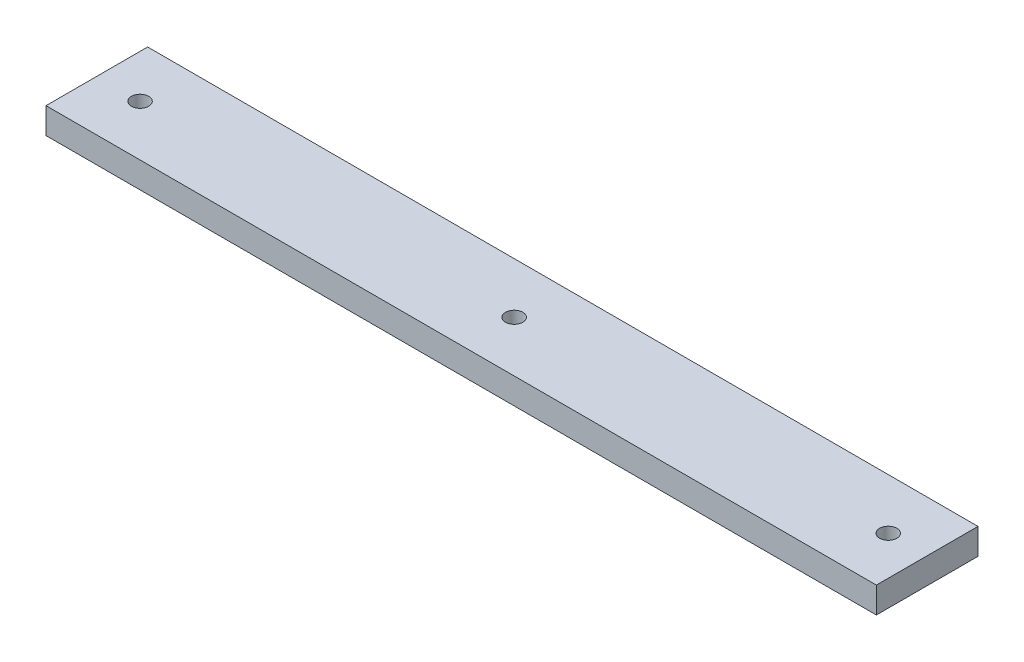
SolidWorks part; units mm, degrees
ref_plane "Front Plane" through (0, 0, 0) normal (0, 0, 1) x (1, 0, 0)
ref_plane "Top Plane" through (0, 0, 0) normal (0, 1, 0) x (1, 0, 0)
ref_plane "Right Plane" through (0, 0, 0) normal (1, 0, 0) x (0, 0, -1)
sketch "Sketch1" plane through (0, 0, 0) normal (0, 1, 0) x (1, 0, 0)
  line L1 (304.8, -37.3062) -> (-304.8, -37.3063)
  line L2 (304.8, -37.3062) -> (304.8, 37.3063)
  line L3 (304.8, 37.3063) -> (-304.8, 37.3062)
  line L4 (-304.8, -37.3063) -> (-304.8, 37.3062)
  line L5 (304.8, -37.3062) -> (-304.8, 37.3062) construction
  line L6 (304.8, 37.3063) -> (-304.8, -37.3063) construction
  point P0 (0, 0)
  dimension "D1" = 609.6
  dimension "D2" = 74.6125
extrude "Boss-Extrude1" add sketch "Sketch1" along normal blind 19.05
sketch "Sketch2" plane through (0, 0, 0) normal (0, -1, 0) x (1, 0, 0)
  line L0 (304.8, 0) -> (1.5875, 0) construction
  line L1 (304.8, 37.3062) -> (304.8, -37.3063) construction
  circle A0 centre (1.5875, 0) radius 3.175
  dimension "D2" = 6.35
  dimension "D1" = 303.2125
extrude "Cut-Extrude1" cut sketch "Sketch2" against normal blind 9.525
sketch "Sketch4" plane through (0, 0, 0) normal (0, -1, 0) x (1, 0, 0)
  circle A0 centre (1.5875, 0) radius 6.35
  dimension "D1" = 12.7
extrude "Cut-Extrude2" cut sketch "Sketch4" against normal blind 9.525 from offset 9.525 offset against normal yes
sketch "Sketch5" plane through (0, 0, 0) normal (0, -1, 0) x (1, 0, 0)
  line L0 (1.5875, 0) -> (276.225, 0) construction
  circle A0 centre (276.225, 0) radius 3.175
  dimension "D2" = 6.35
  dimension "D1" = 274.6375
extrude "Cut-Extrude3" cut sketch "Sketch5" against normal blind 9.525
sketch "Sketch6" plane through (0, 0, 0) normal (0, -1, 0) x (1, 0, 0)
  circle A0 centre (276.225, 0) radius 6.35
  dimension "D1" = 12.7
extrude "Cut-Extrude4" cut sketch "Sketch6" against normal blind 9.525 from offset 9.525 offset against normal yes
sketch "Sketch7" plane through (0, 0, 0) normal (0, -1, 0) x (1, 0, 0)
  line L0 (1.5875, 0) -> (-273.05, 0) construction
  circle A0 centre (-273.05, 0) radius 3.175
  dimension "D2" = 6.35
  dimension "D1" = 274.6375
extrude "Cut-Extrude5" cut sketch "Sketch7" against normal blind 9.525
sketch "Sketch8" plane through (0, 0, 0) normal (0, -1, 0) x (1, 0, 0)
  circle A0 centre (-273.05, 0) radius 6.35
  dimension "D1" = 12.7
extrude "Cut-Extrude6" cut sketch "Sketch8" against normal blind 9.525 from offset 9.525 offset against normal yes
